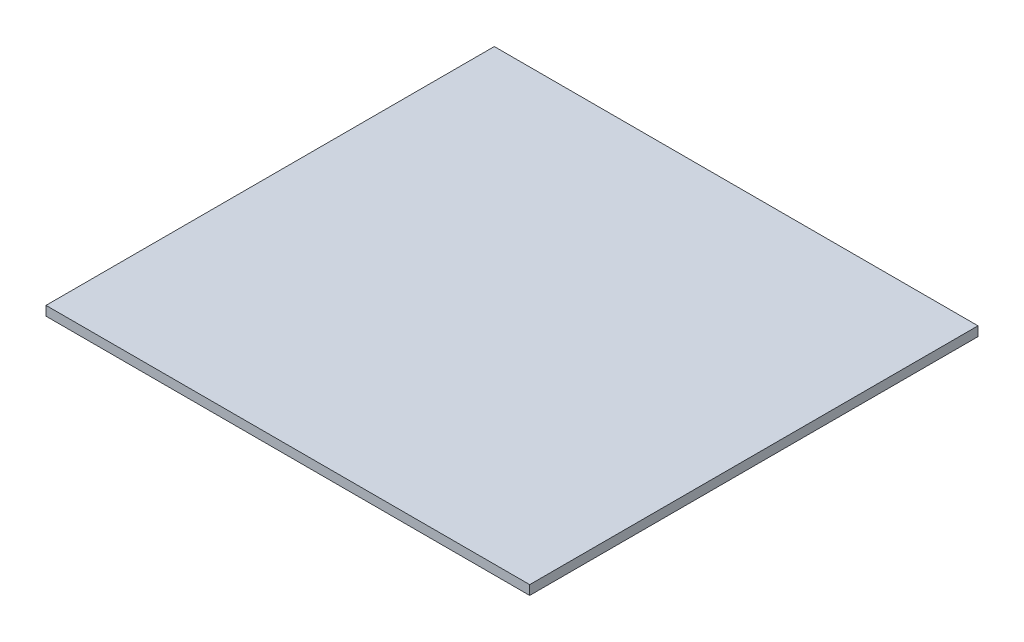
SolidWorks part; units mm, degrees
ref_plane "Front Plane" through (0, 0, 0) normal (0, 0, 1) x (1, 0, 0)
ref_plane "Top Plane" through (0, 0, 0) normal (0, 1, 0) x (1, 0, 0)
ref_plane "Right Plane" through (0, 0, 0) normal (1, 0, 0) x (0, 0, -1)
sketch "Sketch1" plane through (0, 0, 0) normal (0, 1, 0) x (1, 0, 0)
  line L0 (-1266.0759, -965.078) -> (816.7241, -965.078)
  line L1 (-1266.0759, -965.078) -> (-1266.0759, 965.322)
  line L2 (-1266.0759, 965.322) -> (816.7241, 965.322)
  line L3 (816.7241, -965.078) -> (816.7241, 965.322)
  dimension "D1" = 1930.4
  dimension "D2" = 2082.8
extrude "Boss-Extrude1" add sketch "Sketch1" along normal blind 40.4812
